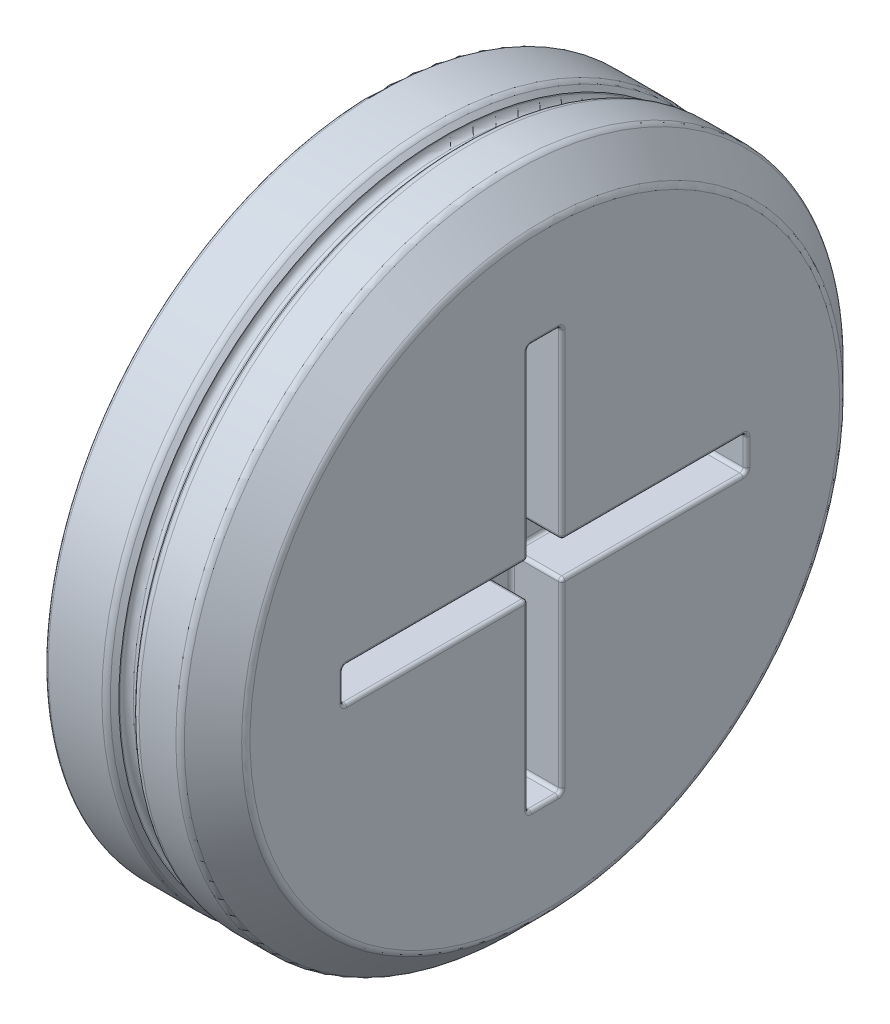
SolidWorks part; units mm, degrees
material "moto_grey"
ref_plane "Front Plane" through (0, 0, 0) normal (0, 0, 1) x (1, 0, 0)
ref_plane "Top Plane" through (0, 0, 0) normal (0, 1, 0) x (1, 0, 0)
ref_plane "Right Plane" through (0, 0, 0) normal (1, 0, 0) x (0, 0, -1)
sketch "Sketch1" plane through (0, 0, 0) normal (1, 0, 0) x (0, 0, -1)
  circle A0 centre (0, 0) radius 8.875
  circle A1 centre (0, 0) radius 9.875
  dimension "D1" = 17.75
  dimension "D2" = 1
extrude "Boss-Extrude1" add sketch "Sketch1" against normal blind 2
sketch "Sketch2" plane through (0, 0, 0) normal (1, 0, 0) x (0, 0, -1)
  circle A0 centre (0, 0) radius 8.875
extrude "Boss-Extrude2" add sketch "Sketch2" against normal blind 0.5
sketch "Sketch3" plane through (0, 0, 0) normal (1, 0, 0) x (0, 0, -1)
  circle A0 centre (0, 0) radius 9.875
  circle A1 centre (0, 0) radius 9.4432
  circle A2 centre (0, 0) radius 9.4432
extrude "Boss-Extrude4" add sketch "Sketch3" along normal blind 0.5 contours A1
sketch "Sketch4" plane through (0.5, 0, 0) normal (1, 0, 0) x (0, 0, -1)
  circle A0 centre (0, 0) radius 9.875
extrude "Boss-Extrude5" add sketch "Sketch4" along normal blind 2.5
chamfer "Chamfer1" distance 0.2 angle 45 2 edges at (0.5, 0, -9.875) (0, 0, -9.875)
fillet "Fillet1" radius 0.2 2 edges at (0.5, 0, -9.4432) (0, 0, -9.4432)
chamfer "Chamfer2" distance 1 angle 45 1 edges at (3, 0, -9.875)
fillet "Fillet3" radius 0.25 2 edges at (3, 0, -8.875) (2, 0, -9.875)
fillet "Fillet4" radius 0.25 2 edges at (-0.2, 0, -9.875) (0.7, 0, -9.875)
sketch "Sketch5" plane through (3, 0, 0) normal (1, 0, 0) x (0, 0, -1)
  line L1 (-6, -0.5) -> (6, -0.5)
  line L2 (-6, -0.5) -> (-6, 0.5)
  line L3 (-6, 0.5) -> (6, 0.5)
  line L4 (6, -0.5) -> (6, 0.5)
  line L5 (-6, -0.5) -> (6, 0.5) construction
  line L6 (-6, 0.5) -> (6, -0.5) construction
  line L7 (-0.5, -6) -> (0.5, -6)
  line L8 (-0.5, -6) -> (-0.5, 6)
  line L9 (-0.5, 6) -> (0.5, 6)
  line L10 (0.5, -6) -> (0.5, 6)
  line L11 (-0.5, -6) -> (0.5, 6) construction
  line L12 (-0.5, 6) -> (0.5, -6) construction
  point P0 (0, 0)
  point P6 (0, 0)
  dimension "D1" = 1
  dimension "D2" = 12
  dimension "D3" = 1
  dimension "D4" = 12
extrude "Cut-Extrude1" cut sketch "Sketch5" against normal blind 1.5 contours L1 L10 L3 L8 | L7 L10 L1 L8 | L10 L1 L4 L3 | L3 L10 L9 L8 | L1 L8 L3 L2
fillet "Fillet5" radius 0.1 36 edges at (2.25, 6, 0.5) (2.25, -0.5, 6) (2.25, -0.5, 0.5) (2.25, -0.5, -0.5) (2.25, 6, -0.5) (2.25, 0.5, -0.5) (2.25, 0.5, 0.5) (2.25, 0.5, 6) (2.25, -6, 0.5) (2.25, -6, -0.5) (2.25, -0.5, -6) (2.25, 0.5, -6) (3, -3.25, 0.5) (3, -6, 0) (3, -3.25, -0.5) (3, -0.5, -3.25) (3, 0, -6) (3, 0.5, -3.25) (3, 3.25, -0.5) (3, 6, 0) (3, 3.25, 0.5) (3, 0.5, 3.25) (3, 0, 6) (3, -0.5, 3.25) (1.5, 0, 6) (1.5, 0.5, 3.25) (1.5, 3.25, 0.5) (1.5, 6, 0) (1.5, 3.25, -0.5) (1.5, 0.5, -3.25) (1.5, 0, -6) (1.5, -0.5, -3.25) (1.5, -3.25, -0.5) (1.5, -6, 0) (1.5, -3.25, 0.5) (1.5, -0.5, 3.25)
fillet "Fillet6" radius 0.1 1 edges at (-2, 0, -9.875)
